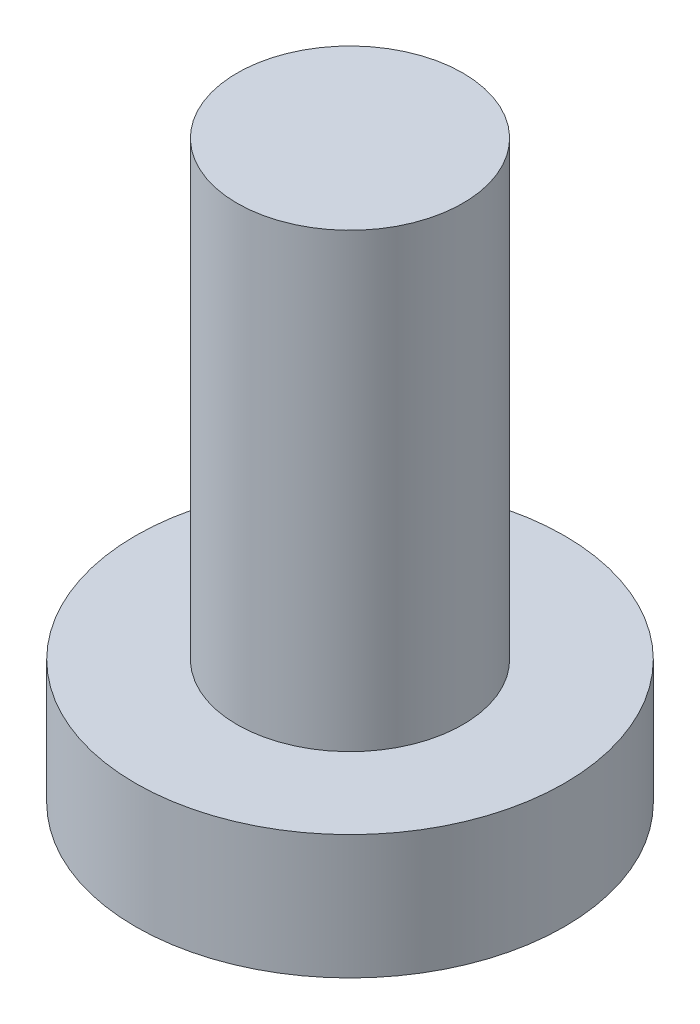
SolidWorks part; units mm, degrees
ref_plane "前视基准面" through (0, 0, 0) normal (0, 0, 1) x (1, 0, 0)
ref_plane "上视基准面" through (0, 0, 0) normal (0, 1, 0) x (1, 0, 0)
ref_plane "右视基准面" through (0, 0, 0) normal (1, 0, 0) x (0, 0, -1)
sketch "草图1" plane through (0, 0, 0) normal (0, 1, 0) x (1, 0, 0)
  circle A0 centre (0, 0) radius 2.85
  dimension "D1" = 5.7
extrude "凸台-拉伸1" add sketch "草图1" along normal blind 1.65
sketch "草图2" plane through (0, 1.65, 0) normal (0, 1, 0) x (1, 0, 0)
  circle A0 centre (0, 0) radius 1.5
  dimension "D1" = 3
extrude "凸台-拉伸2" add sketch "草图2" along normal blind 6
